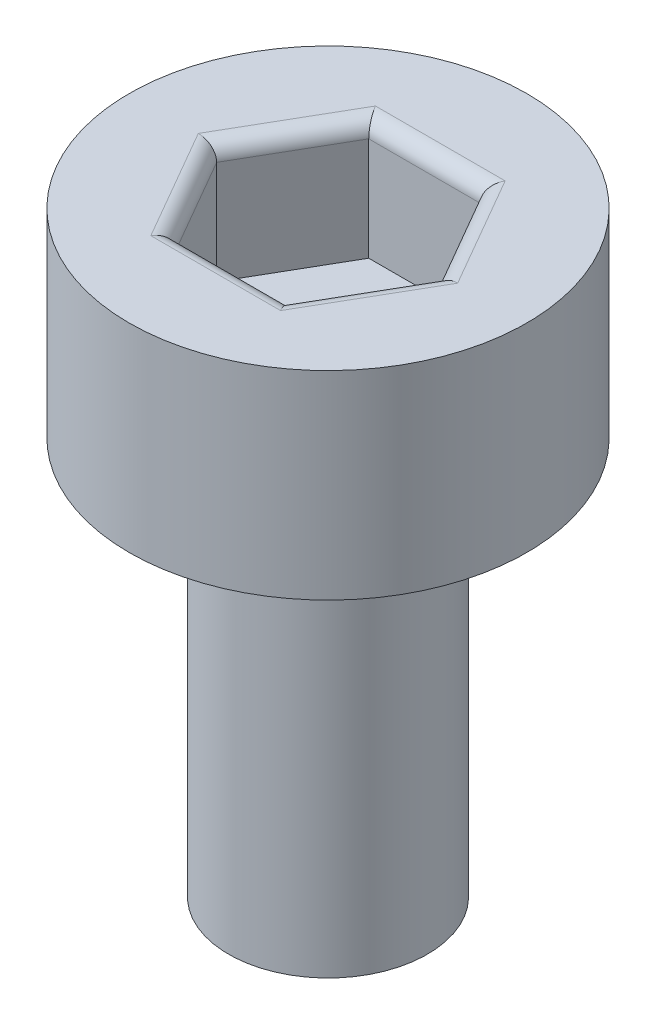
SolidWorks part; units mm, degrees
material "灰铸铁"
ref_plane "前视基准面" through (0, 0, 0) normal (0, 0, 1) x (1, 0, 0)
ref_plane "上视基准面" through (0, 0, 0) normal (0, 1, 0) x (1, 0, 0)
ref_plane "右视基准面" through (0, 0, 0) normal (1, 0, 0) x (0, 0, -1)
other "Configuration Table"
sketch "草图1" plane through (0, 0, 0) normal (0, 1, 0) x (1, 0, 0)
  circle A0 centre (0, 0) radius 2.5
  dimension "D1" = 5
extrude "凸台-拉伸1" add sketch "草图1" along normal blind 2.5
sketch "草图2" plane through (0, 2.5, 0) normal (0, 1, 0) x (1, 0, 0)
  line L0 (-0.7, 1.2124) -> (0.7, 1.2124)
  line L1 (0.7, 1.2124) -> (1.4, 0)
  line L2 (1.4, 0) -> (0.7, -1.2124)
  line L3 (0.7, -1.2124) -> (-0.7, -1.2124)
  line L4 (-0.7, -1.2124) -> (-1.4, 0)
  line L5 (-1.4, 0) -> (-0.7, 1.2124)
  line L6 (-0.7, 1.2124) -> (0.7, -1.2124) construction
  line L7 (-0.7, -1.2124) -> (0.7, 1.2124) construction
  point P2 (0, 0)
  dimension "D1" = 120
  dimension "D2" = 120
  dimension "D3" = 2.8
  dimension "D4" = 2.8
extrude "切除-拉伸1" cut sketch "草图2" against normal blind 1.5 contours L5 L0 L1 L2 L3 L4
sketch "草图5" plane through (0, 0, 0) normal (0, -1, 0) x (1, 0, 0)
  circle A0 centre (0, 0) radius 1.25
  dimension "D1" = 2.5
extrude "凸台-拉伸2" add sketch "草图5" along normal blind 5
fillet "圆角1" radius 0.2 6 edges at (0, 2.5, -1.2124) (-1.05, 2.5, -0.6062) (-1.05, 2.5, 0.6062) (1.05, 2.5, -0.6062) (0, 2.5, 1.2124) (1.05, 2.5, 0.6062)
